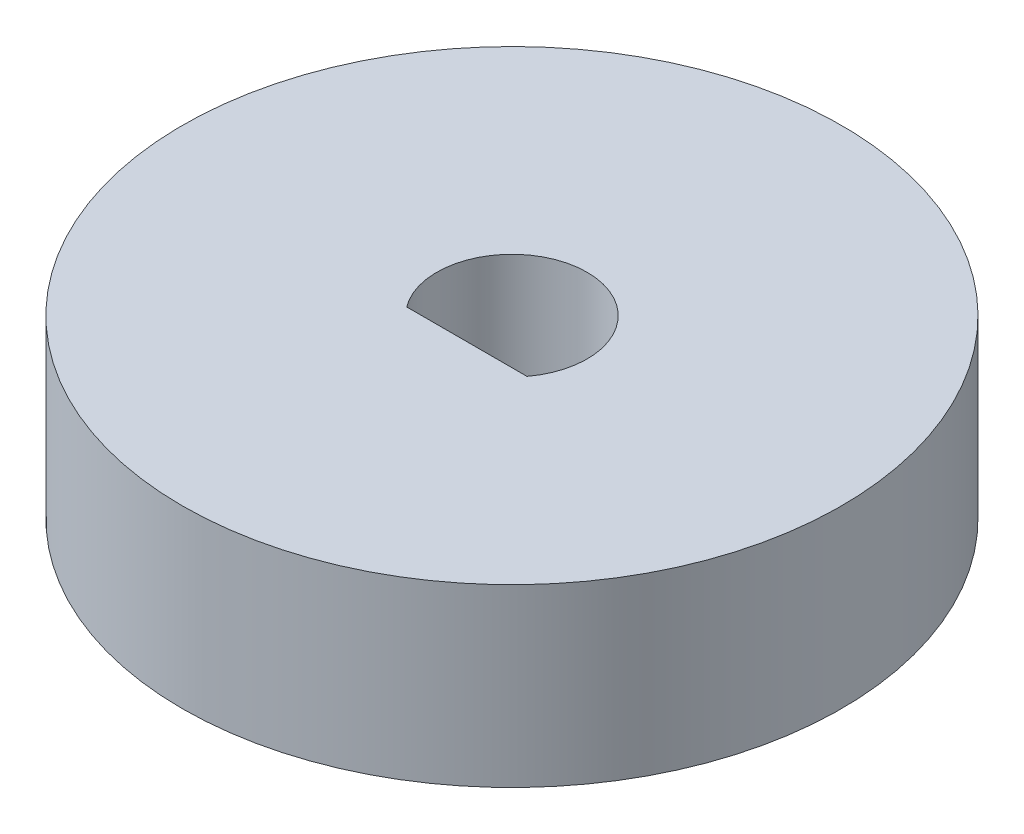
SolidWorks part; units mm, degrees
ref_plane "Front Plane" through (0, 0, 0) normal (0, 0, 1) x (1, 0, 0)
ref_plane "Top Plane" through (0, 0, 0) normal (0, 1, 0) x (1, 0, 0)
ref_plane "Right Plane" through (0, 0, 0) normal (1, 0, 0) x (0, 0, -1)
sketch "Sketch1" plane through (0, 0, 0) normal (0, 1, 0) x (1, 0, 0)
  circle A0 centre (0, 0) radius 10.9601
  dimension "D1" = 21.9202
extrude "Boss-Extrude1" add sketch "Sketch1" along normal blind 5.842
sketch "Sketch3" plane through (0, 5.842, 0) normal (0, 1, 0) x (1, 0, 0)
  line L0 (-2, -1.5) -> (2, -1.5)
  arc A0 (-2, -1.5) -> (2, -1.5) centre (0, 0) cw
  dimension "D2" = 2.5
  dimension "D1" = 1.5
extrude "Cut-Extrude1" cut sketch "Sketch3" against normal through all
